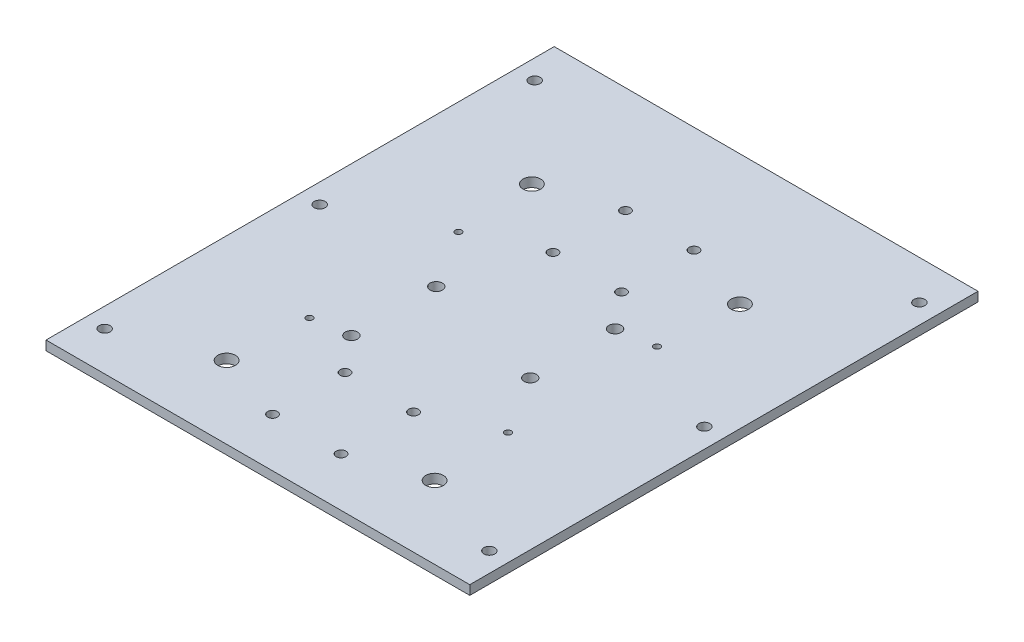
SolidWorks part; units mm, degrees
material "Acrylic (Medium-high impact)"
ref_plane "Front Plane" through (0, 0, 0) normal (0, 0, 1) x (1, 0, 0)
ref_plane "Top Plane" through (0, 0, 0) normal (0, 1, 0) x (1, 0, 0)
ref_plane "Right Plane" through (0, 0, 0) normal (1, 0, 0) x (0, 0, -1)
sketch "Sketch1" plane through (0, 0, 0) normal (0, 1, 0) x (1, 0, 0)
  line L0 (0, 43.4) -> (0, 0) construction
  line L1 (14.724, 125.484) -> (14.724, 88.4) construction
  line L2 (-76.15, 179.916) -> (140.65, 179.916)
  line L3 (-76.15, 179.916) -> (-76.15, -80.084)
  line L4 (-76.15, -80.084) -> (140.65, -80.084)
  line L5 (140.65, 179.916) -> (140.65, -80.084)
  line L6 (14.724, 88.4) -> (49.776, 88.4) construction
  line L7 (49.776, 88.4) -> (49.776, 125.484) construction
  line L8 (49.776, 125.484) -> (14.724, 125.484) construction
  line L9 (14.724, -18) -> (14.724, -55.084) construction
  line L10 (14.724, -55.084) -> (49.776, -55.084) construction
  line L11 (49.776, -55.084) -> (49.776, -18) construction
  line L12 (49.776, -18) -> (14.724, -18) construction
  line L13 (32.25, 179.916) -> (32.25, -80.084) construction
  line L14 (0, 43.4) -> (64.5, 70.4) construction
  line L15 (83.05, 73.3) -> (85.463, 113.292) construction
  line L16 (-18.55, 73.3) -> (83.05, 73.3) construction
  line L17 (-18.55, 73.3) -> (-18.55, -2.9) construction
  line L18 (-18.55, -2.9) -> (83.05, -2.9) construction
  line L19 (83.05, 73.3) -> (83.05, -2.9) construction
  line L20 (83.05, -2.9) -> (85.463, -42.892) construction
  circle A0 centre (0, 0) radius 3.15
  circle A1 centre (64.5, 27) radius 3.15
  circle A2 centre (0, 43.4) radius 3.15
  circle A3 centre (64.5, 70.4) radius 3.15
  circle A4 centre (14.724, 125.484) radius 2.5
  circle A5 centre (49.776, 125.484) radius 2.5
  circle A6 centre (14.724, 88.4) radius 2.5
  circle A7 centre (49.776, 88.4) radius 2.5
  circle A8 centre (-20.963, 113.292) radius 4.5
  circle A9 centre (85.463, 113.292) radius 4.5
  circle A10 centre (14.724, -18) radius 2.5
  circle A11 centre (49.776, -18) radius 2.5
  circle A12 centre (14.724, -55.084) radius 2.5
  circle A13 centre (49.776, -55.084) radius 2.5
  circle A14 centre (-20.963, -42.892) radius 4.5
  circle A15 centre (85.463, -42.892) radius 4.5
  circle A16 centre (-66.15, 159.916) radius 2.8
  circle A17 centre (-66.15, 49.916) radius 2.8
  circle A18 centre (-66.15, -60.084) radius 2.8
  circle A19 centre (130.65, -60.084) radius 2.8
  circle A20 centre (130.65, 49.916) radius 2.8
  circle A21 centre (130.65, 159.916) radius 2.8
  circle A22 centre (-18.55, 73.3) radius 1.65
  circle A23 centre (83.05, 73.3) radius 1.65
  circle A24 centre (-18.55, -2.9) radius 1.65
  circle A25 centre (83.05, -2.9) radius 1.65
  point P39 (32.25, 56.9)
  point P40 (32.25, 125.484)
  point P41 (32.25, -18)
  point P62 (32.25, 73.3)
  dimension "D1" = 6.3
  dimension "D2" = 6.3
  dimension "D3" = 6.3
  dimension "D4" = 6.3
  dimension "D16" = 9
  dimension "D17" = 5
  dimension "D18" = 5
  dimension "D19" = 5
  dimension "D20" = 5
  dimension "D21" = 9
  dimension "D29" = 9
  dimension "D30" = 5
  dimension "D31" = 5
  dimension "D32" = 5
  dimension "D33" = 5
  dimension "D34" = 18
  dimension "D38" = 5.6
  dimension "D39" = 5.6
  dimension "D40" = 5.6
  dimension "D41" = 5.6
  dimension "D42" = 5.6
  dimension "D43" = 5.6
  dimension "D56" = 9
  dimension "D57" = 3.3
  dimension "D58" = 3.3
  dimension "D59" = 3.3
  dimension "D60" = 3.3
  dimension "D5" = 64.5
  dimension "D6" = 27
  dimension "D7" = 16.4
  dimension "D8" = 27
  dimension "D9" = 64.5
  dimension "D10" = 35.052
  dimension "D11" = 37.084
  dimension "D12" = 35.687
  dimension "D13" = 35.687
  dimension "D14" = 12.192
  dimension "D15" = 12.192
  dimension "D22" = 18
  dimension "D23" = 12.192
  dimension "D24" = 12.192
  dimension "D25" = 37.084
  dimension "D26" = 35.052
  dimension "D27" = 35.687
  dimension "D28" = 35.687
  dimension "D35" = 216.8
  dimension "D36" = 260
  dimension "D37" = 25
  dimension "D44" = 10
  dimension "D45" = 20
  dimension "D46" = 10
  dimension "D47" = 130
  dimension "D48" = 20
  dimension "D49" = 10
  dimension "D50" = 10
  dimension "D51" = 20
  dimension "D52" = 10
  dimension "D53" = 130
  dimension "D54" = 10
  dimension "D55" = 20
  dimension "D61" = 76.2
  dimension "D63" = 101.6
extrude "Boss-Extrude1" add sketch "Sketch1" along normal blind 4.7625
